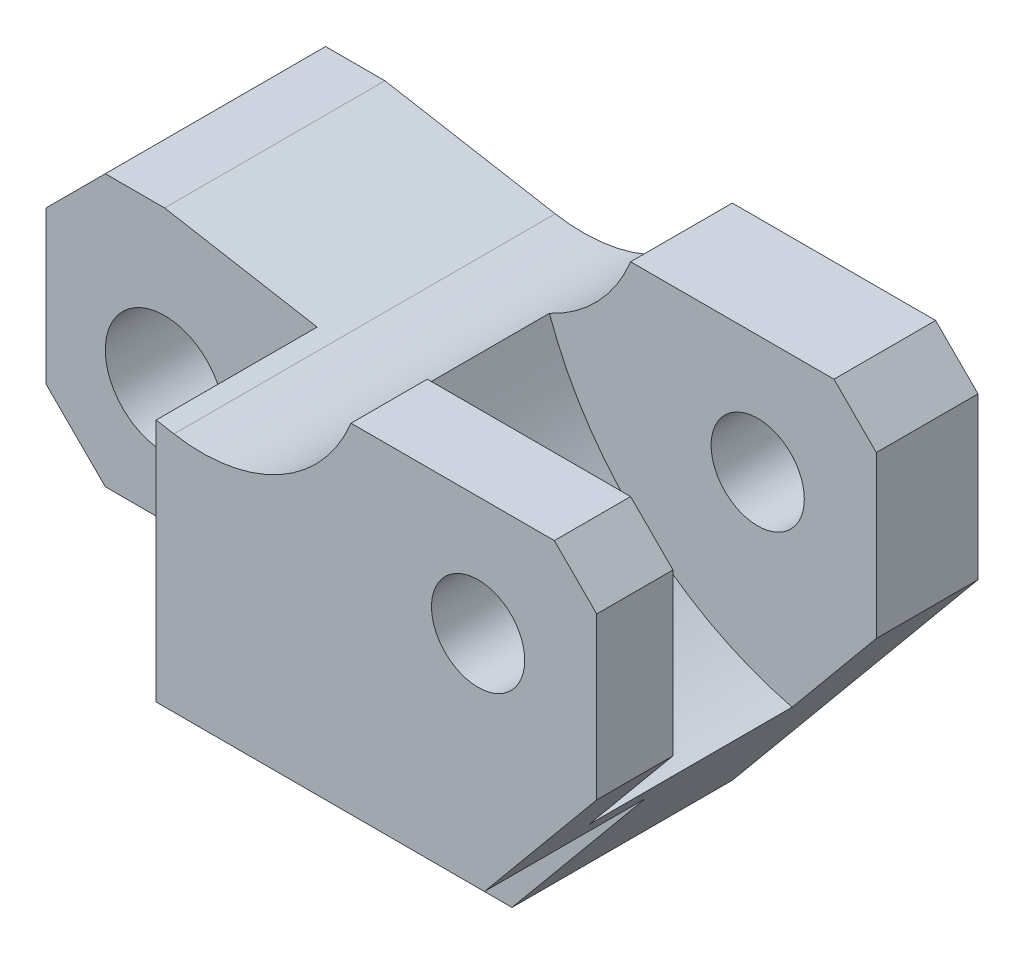
SolidWorks part; units mm, degrees
material "AISI 1020"
ref_plane "Front Plane" through (0, 0, 0) normal (0, 0, 1) x (1, 0, 0)
ref_plane "Top Plane" through (0, 0, 0) normal (0, 1, 0) x (1, 0, 0)
ref_plane "Right Plane" through (0, 0, 0) normal (1, 0, 0) x (0, 0, -1)
sketch "Esquisse1" plane through (0, 0, 0) normal (0, 0, 1) x (1, 0, 0)
  line L0 (0, 0) -> (6.166, 0)
  line L1 (6.166, 0) -> (35.166, 35)
  line L2 (35.166, 35) -> (35.166, 54)
  line L3 (35.166, 54) -> (30.166, 59)
  line L4 (30.166, 59) -> (6.166, 59)
  line L11 (-14.7299, 47.4551) -> (-34.834, 51)
  line L12 (-34.834, 51) -> (-41.834, 51)
  line L13 (-41.834, 51) -> (-48.834, 44)
  line L14 (-48.834, 44) -> (-48.834, 26)
  line L15 (-48.834, 26) -> (-41.834, 19)
  line L16 (-41.834, 19) -> (-11.7214, 19)
  arc A3 (6.166, 59) -> (-14.7299, 47.4551) centre (-11.4306, 66.1665) cw
  arc A4 (-11.7214, 19) -> (-6.7758, 14.7353) centre (-11.7214, 14) cw
  arc A5 (-6.7758, 14.7353) -> (0, 0) centre (21.9089, 19) ccw
  point P32 (3.083, 0)
  dimension "D8" = 19
  dimension "D17" = 5
  dimension "D18" = 29
  dimension "D1" = 59
  dimension "D2" = 5
  dimension "D3" = 45
  dimension "D4" = 29
  dimension "D5" = 24
  dimension "D6" = 29
  dimension "D7" = 84
  dimension "D9" = 10
  dimension "D10" = 7
  dimension "D11" = 45
  dimension "D12" = 14
  dimension "D14" = 7
  dimension "D15" = 45
  dimension "D16" = 19
  dimension "D19" = 19
  dimension "D13" = 32
extrude "Boss.-Extru.1" add sketch "Esquisse1" along normal mid plane 45
sketch "Esquisse2" plane through (0, 0, 22.5) normal (0, 0, 1) x (1, 0, 0)
  line L0 (-48.834, 44) -> (-48.834, 26) construction
  line L1 (-41.834, 19) -> (-11.7214, 19) construction
  circle A0 centre (-34.834, 33) radius 7
  dimension "D1" = 14
  dimension "D2" = 14
  dimension "D3" = 14
extrude "Enlèv. mat.-Extru.1" cut sketch "Esquisse2" against normal through all
sketch "Esquisse4" plane through (0, 0, 22.5) normal (0, 0, 1) x (1, 0, 0)
  line L0 (-16.834, 47.8261) -> (-16.834, 19)
  line L1 (-14.7299, 47.4551) -> (-34.834, 51) construction
  line L2 (-41.834, 19) -> (-11.7214, 19) construction
  line L3 (-11.7214, 19) -> (21.9089, 19)
  line L4 (6.166, 0) -> (35.166, 35) construction
  line L5 (35.166, 35) -> (35.166, 54) construction
  line L16 (0, 0) -> (6.166, 0)
  line L17 (6.166, 0) -> (35.166, 35)
  line L18 (35.166, 35) -> (35.166, 54)
  line L19 (35.166, 54) -> (30.166, 59)
  line L20 (30.166, 59) -> (6.166, 59)
  line L21 (-14.7299, 47.4551) -> (-34.834, 51)
  line L22 (-34.834, 51) -> (-41.834, 51)
  line L23 (-41.834, 51) -> (-48.834, 44)
  line L24 (-48.834, 44) -> (-48.834, 26)
  line L25 (-48.834, 26) -> (-41.834, 19)
  line L26 (-41.834, 19) -> (-11.7214, 19)
  line L27 (0, 0) -> (6.166, 0)
  line L28 (6.166, 0) -> (21.9089, 19)
  line L32 (-16.834, 47.8261) -> (-34.834, 51)
  line L33 (-34.834, 51) -> (-41.834, 51)
  line L34 (-41.834, 51) -> (-48.834, 44)
  line L35 (-48.834, 44) -> (-48.834, 26)
  line L36 (-48.834, 26) -> (-41.834, 19)
  line L37 (-41.834, 19) -> (-16.834, 19)
  arc A3 (-6.7758, 14.7353) -> (0, 0) centre (21.9089, 19) ccw
  arc A4 (-14.7299, 47.4551) -> (6.166, 59) centre (-11.4306, 66.1665) ccw
  arc A5 (-6.7758, 14.7353) -> (-11.7214, 19) centre (-11.7214, 14) ccw
  arc A6 (-6.7758, 14.7353) -> (0, 0) centre (21.9089, 19) ccw
  arc A8 (-6.7758, 14.7353) -> (-11.7214, 19) centre (-11.7214, 14) ccw
  dimension "D2" = 52
  dimension "D1" = 0
extrude "Enlèv. mat.-Extru.2" cut sketch "Esquisse4" against normal blind 19
sketch "Esquisse5" plane through (0, 0, 22.5) normal (0, 0, 1) x (1, 0, 0)
  line L0 (21.9089, 19) -> (35.166, 35) construction
  line L1 (30.166, 59) -> (6.166, 59) construction
  line L10 (-16.834, 47.8261) -> (-16.834, 19)
  line L11 (-16.834, 19) -> (21.9089, 19)
  line L12 (21.9089, 19) -> (35.166, 35)
  line L13 (35.166, 35) -> (35.166, 54)
  line L14 (35.166, 54) -> (30.166, 59)
  line L15 (30.166, 59) -> (6.166, 59)
  line L16 (-14.7299, 47.4551) -> (-16.834, 47.8261)
  line L19 (25.2232, 23) -> (35.166, 35)
  line L20 (35.166, 35) -> (35.166, 54)
  line L21 (35.166, 54) -> (30.166, 59)
  line L22 (30.166, 59) -> (6.166, 59)
  arc A0 (-3.4268, 48.9345) -> (25.2232, 23) centre (35.166, 62.7761) ccw
  arc A1 (-14.7299, 47.4551) -> (6.166, 59) centre (-11.4306, 66.1665) ccw construction
  arc A3 (-14.7299, 47.4551) -> (6.166, 59) centre (-11.4306, 66.1665) ccw
  arc A4 (-3.4268, 48.9345) -> (6.166, 59) centre (-11.4306, 66.1665) ccw
  point P10 (0, 0)
  point P11 (-3.4268, 48.9345)
  point P12 (-3.4268, 48.9345)
  point P13 (0, 0)
  point P15 (-3.4268, 48.9345)
  dimension "D1" = 41
  dimension "D2" = 36
  dimension "D3" = 0
extrude "Enlèv. mat.-Extru.3" cut sketch "Esquisse5" along normal blind 24 from offset 33 offset against normal yes
sketch "Esquisse6" plane through (0, 0, 22.5) normal (0, 0, 1) x (1, 0, 0)
  line L0 (35.166, 35) -> (35.166, 54) construction
  line L1 (30.166, 59) -> (6.166, 59) construction
  circle A0 centre (21.166, 45) radius 5.5
  point P4 (0, 0)
  point P6 (22.3142, 49.6991)
  dimension "D1" = 11
  dimension "D2" = 14
  dimension "D3" = 14
extrude "Enlèv. mat.-Extru.4" cut sketch "Esquisse6" against normal through all
equation "\"A\"= 84"
equation "\"B\"= 59"
equation "\"C\"= 45"
equation "\"D1@Esquisse1\"=\"B\""
equation "\"D7@Esquisse1\"=\"A\""
equation "\"D1@Boss.-Extru.1\"=\"C\""
equation "\"D19@Enlèv. mat.-Extru.3\"=\"C\"-12"
